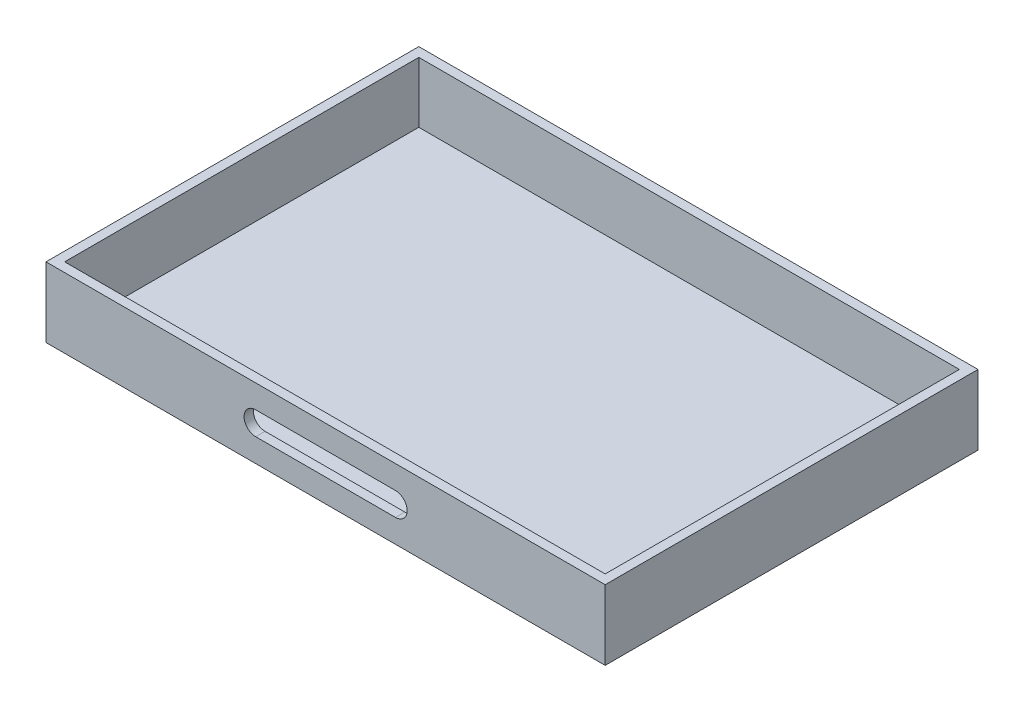
SolidWorks part; units mm, degrees
ref_plane "Plano frontal" through (0, 0, 0) normal (0, 0, 1) x (1, 0, 0)
ref_plane "Plano superior" through (0, 0, 0) normal (0, 1, 0) x (1, 0, 0)
ref_plane "Plano direito" through (0, 0, 0) normal (1, 0, 0) x (0, 0, -1)
sketch "Esboço1" plane through (0, 0, 0) normal (0, 1, 0) x (1, 0, 0)
  line L1 (-60, -40) -> (60, -40)
  line L2 (-60, -40) -> (-60, 40)
  line L3 (-60, 40) -> (60, 40)
  line L4 (60, -40) -> (60, 40)
  line L5 (-60, -40) -> (60, 40) construction
  line L6 (-60, 40) -> (60, -40) construction
  line L11 (-58, -38.6667) -> (58, 38.6667) construction
  line L12 (-58, 38.6667) -> (58, -38.6667) construction
  point P0 (0, 0)
  point P6 (0, 0)
  dimension "D1" = 120
  dimension "D2" = 80
extrude "Ressalto-extrusão2" add sketch "Esboço1" along normal blind 2
sketch "Esboço2" plane through (0, 2, 0) normal (0, 1, 0) x (1, 0, 0)
  line L1 (-58, -38) -> (58, -38)
  line L2 (-58, -38) -> (-58, 38)
  line L3 (-58, 38) -> (58, 38)
  line L4 (58, -38) -> (58, 38)
  line L5 (-58, -38) -> (58, 38) construction
  line L6 (-58, 38) -> (58, -38) construction
  point P0 (0, 0)
  dimension "D1" = 116
  dimension "D2" = 76
extrude "Extrusão-Fina1" add sketch "Esboço2" along normal blind 13 thin
sketch "Esboço3" plane through (0, 0, 40) normal (0, 0, 1) x (1, 0, 0)
  line L0 (0, 0) -> (0, 15) construction
  line L1 (-60, 0) -> (60, 0) construction
  line L2 (-60, 15) -> (60, 15) construction
  line L3 (-60, 7.5) -> (60, 7.5) construction
  line L4 (-60, 15) -> (-60, 0) construction
  line L5 (60, 15) -> (60, 0) construction
  line L6 (-15, 7.5) -> (15, 7.5) construction
  line L7 (-15, 10) -> (15, 10)
  line L8 (-15, 5) -> (15, 5)
  arc A0 (-15, 10) -> (-15, 5) centre (-15, 7.5) ccw
  arc A1 (15, 5) -> (15, 10) centre (15, 7.5) ccw
  point P14 (0, 7.5)
  dimension "D1" = 30
  dimension "D2" = 5
extrude "Corte-extrusão1" cut sketch "Esboço3" against normal up to surface (2 mm away) up to face at (0, 8.5, 38)
